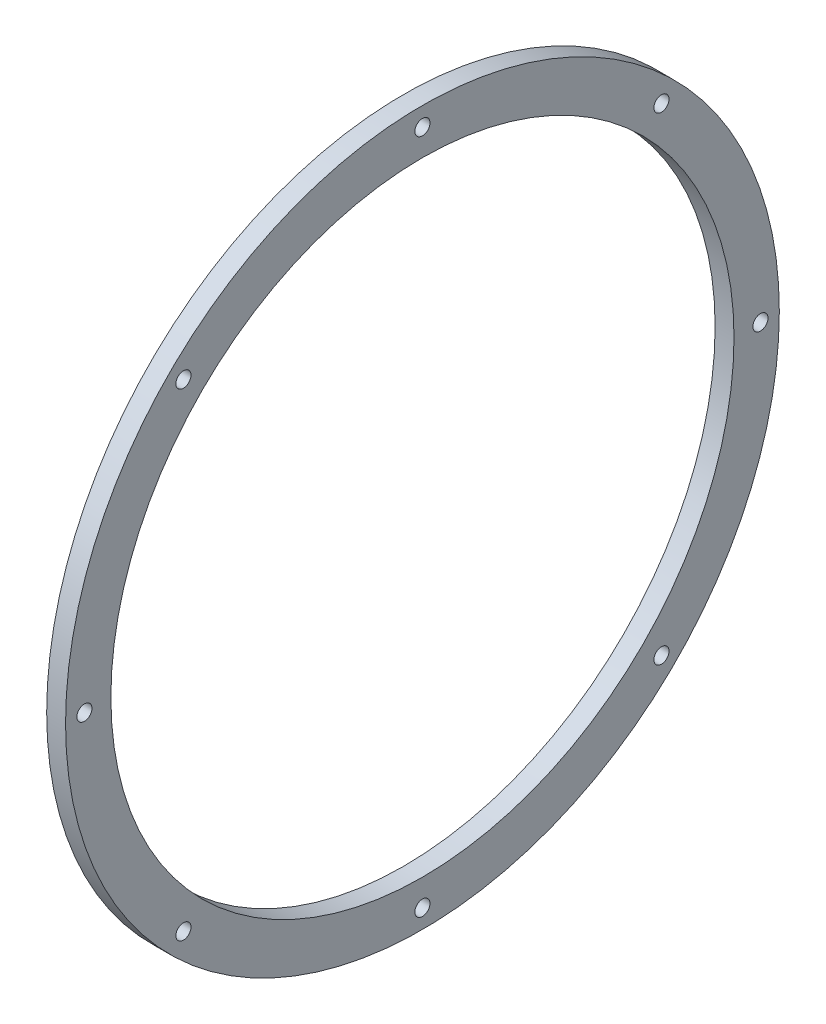
SolidWorks part; units mm, degrees
material "1023 Carbon Steel Sheet (SS)"
ref_plane "Front Plane" through (0, 0, 0) normal (0, 0, 1) x (1, 0, 0)
ref_plane "Top Plane" through (0, 0, 0) normal (0, 1, 0) x (1, 0, 0)
ref_plane "Right Plane" through (0, 0, 0) normal (1, 0, 0) x (0, 0, -1)
sketch "Sketch1" plane through (0, 0, 0) normal (0, 0, 1) x (1, 0, 0)
  line L0 (-206.0179, 0) -> (5794.8787, 0) construction
  line L1 (-86, 82.5) -> (-81, 82.5)
  line L8 (-86, 82.5) -> (-81, 82.5)
  line L9 (-86, 82.5) -> (-86, 94.5)
  line L10 (-86, 94.5) -> (-81, 94.5)
  line L11 (-81, 82.5) -> (-81, 94.5)
  dimension "D1" = 82.5
  dimension "D8" = 12
  dimension "D9" = 5
revolve "Revolve1" add sketch "Sketch1" angle 360 about L0
sketch "Sketch2" plane through (-86, 0, 0) normal (-1, 0, 0) x (0, 0, 1)
  circle A0 centre (0, 89.5) radius 2
  dimension "D1" = 4
  dimension "D2" = 89.5
extrude "Cut-Extrude1" cut sketch "Sketch2" against normal blind 30
pattern_circular "CirPattern1" count 8 over 360 about axis through (0, 0, 0) along (1, 0, 0) of "Cut-Extrude1"
